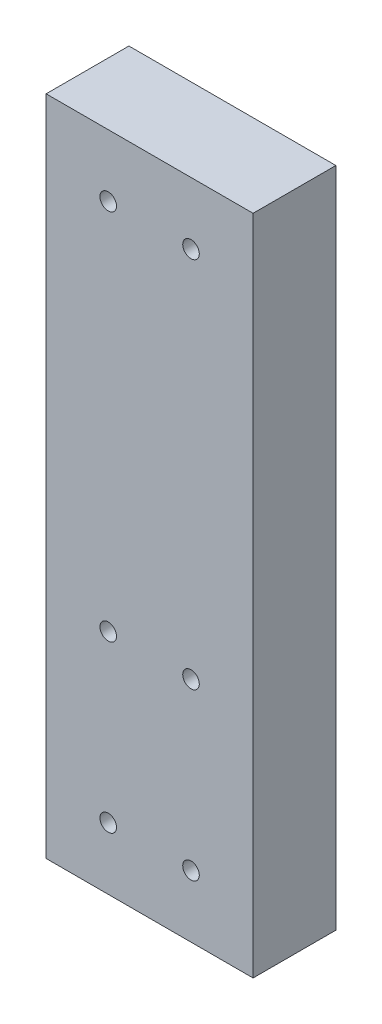
SolidWorks part; units mm, degrees
material "Balsa"
ref_plane "Plan de face" through (0, 0, 0) normal (0, 0, 1) x (1, 0, 0)
ref_plane "Plan de dessus" through (0, 0, 0) normal (0, 1, 0) x (1, 0, 0)
ref_plane "Plan de droite" through (0, 0, 0) normal (1, 0, 0) x (0, 0, -1)
sketch "Sketch1" plane through (0, 0, 0) normal (0, 0, 1) x (1, 0, 0)
  line L1 (0, 0) -> (25, 0)
  line L2 (0, 0) -> (0, -80)
  line L3 (0, -80) -> (25, -80)
  line L4 (25, 0) -> (25, -80)
  dimension "D1" = 25
  dimension "D2" = 80
extrude "Boss-Extrude1" add sketch "Sketch1" along normal blind 10
sketch "Sketch2" plane through (0, 0, 10) normal (0, 0, 1) x (1, 0, 0)
  line L0 (12.5, 0) -> (12.5, -80) construction
  line L1 (25, 0) -> (0, 0) construction
  line L2 (0, -80) -> (25, -80) construction
  line L3 (0, -7.5) -> (25, -7.5) construction
  line L4 (0, 0) -> (0, -80) construction
  line L5 (25, -80) -> (25, 0) construction
  line L6 (0, -72.5) -> (25, -72.5) construction
  line L7 (0, -52.5) -> (25, -52.5) construction
  line L8 (7.5, 0) -> (7.5, -80) construction
  circle A0 centre (7.5, -7.5) radius 1
  circle A1 centre (7.5, -72.5) radius 1
  circle A2 centre (7.5, -52.5) radius 1
  circle A3 centre (17.5, -72.5) radius 1
  circle A4 centre (17.5, -52.5) radius 1
  circle A5 centre (17.5, -7.5) radius 1
  dimension "D2" = 7.5
  dimension "D3" = 2
  dimension "D4" = 2
  dimension "D8" = 2
  dimension "D1" = 7.5
  dimension "D5" = 5
  dimension "D7" = 52.5
extrude "Cut-Extrude1" cut sketch "Sketch2" against normal through all contours A2 | A1 | A0 | A5 | A4 | A3
